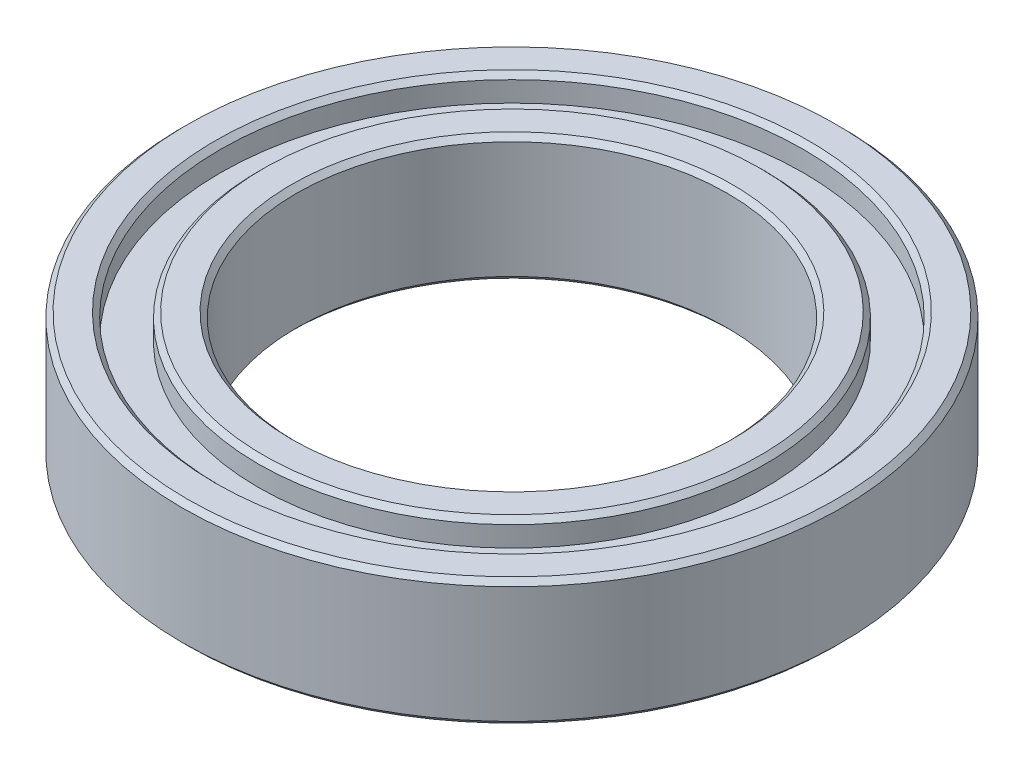
SolidWorks part; units mm, degrees
ref_plane "Front Plane" through (0, 0, 0) normal (0, 0, 1) x (1, 0, 0)
ref_plane "Top Plane" through (0, 0, 0) normal (0, 1, 0) x (1, 0, 0)
ref_plane "Right Plane" through (0, 0, 0) normal (1, 0, 0) x (0, 0, -1)
sketch "Sketch1" plane through (0, 0, 0) normal (0, 1, 0) x (1, 0, 0)
  circle A0 centre (0, 0) radius 13
  circle A1 centre (0, 0) radius 8.5
  dimension "D1" = 26
  dimension "D2" = 17
extrude "Boss-Extrude1" add sketch "Sketch1" along normal blind 5
sketch "Sketch2" plane through (0, 5, 0) normal (0, 1, 0) x (1, 0, 0)
  circle A0 centre (0, 0) radius 10
  circle A1 centre (0, 0) radius 11.5
  dimension "D1" = 23
  dimension "D2" = 20
extrude "Cut-Extrude1" cut sketch "Sketch2" against normal blind 1
sketch "Sketch3" plane through (0, 0, 0) normal (0, -1, 0) x (1, 0, 0)
  circle A0 centre (0, 0) radius 10
  circle A1 centre (0, 0) radius 11.5
  dimension "D1" = 23
  dimension "D2" = 20
extrude "Cut-Extrude2" cut sketch "Sketch3" against normal blind 1
chamfer "Chamfer1" distance 0.2 angle 45 8 edges at (0, 5, 10) (0, 5, 8.5) (0, 5, 13) (0, 5, 11.5) (0, 0, 13) (0, 0, -11.5) (0, 0, -10) (0, 0, 8.5)
